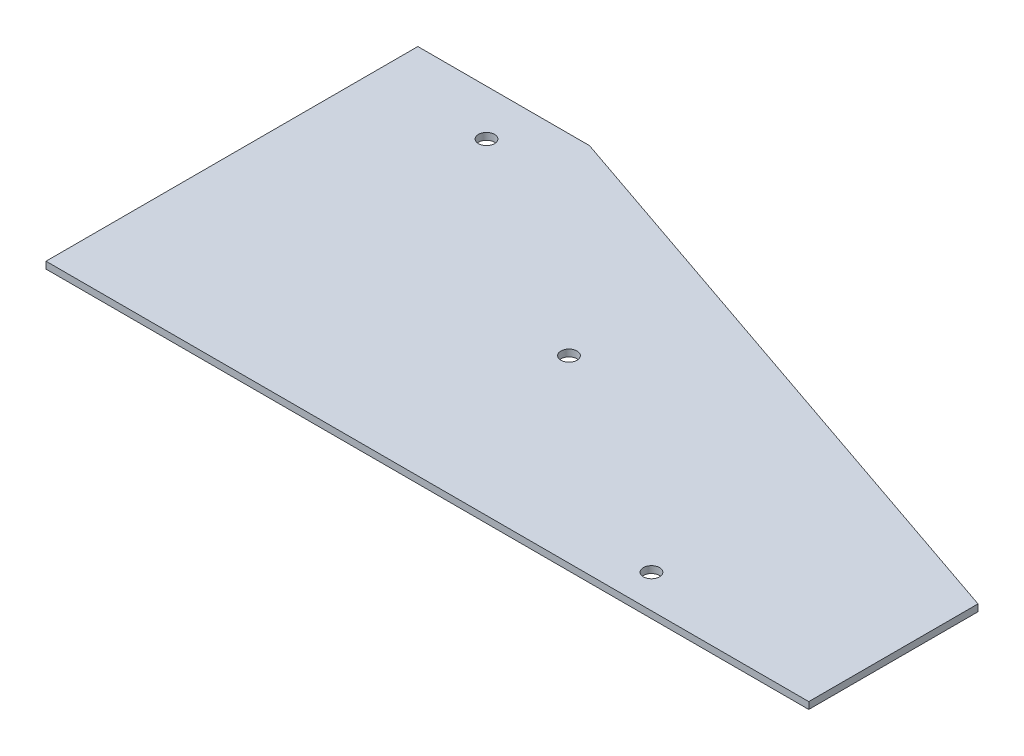
SolidWorks part; units mm, degrees
material "Pine"
ref_plane "Front Plane" through (0, 0, 0) normal (0, 0, 1) x (1, 0, 0)
ref_plane "Top Plane" through (0, 0, 0) normal (0, 1, 0) x (1, 0, 0)
ref_plane "Right Plane" through (0, 0, 0) normal (1, 0, 0) x (0, 0, -1)
sketch "Sketch1" plane through (0, 0, 0) normal (0, 1, 0) x (1, 0, 0)
  line L0 (2032, 450.85) -> (457.2, 990.6)
  line L1 (0, 0) -> (2032, 0)
  line L2 (0, 0) -> (0, 990.6)
  line L3 (0, 990.6) -> (2032, 990.6) construction
  line L4 (2032, 0) -> (2032, 990.6) construction
  line L5 (0, 990.6) -> (457.2, 990.6)
  line L6 (2032, 450.85) -> (2032, 0)
  dimension "D1" = 2032
  dimension "D2" = 990.6
  dimension "D3" = 457.2
  dimension "D4" = 450.85
extrude "Boss-Extrude1" add sketch "Sketch1" along normal blind 18.2562
hole_wizard "1 (1.69) Diameter Hole1" positions "Sketch2" profile "Sketch3" hole size "1" standard "ANSI Inch" end condition through all
sketch "Sketch2" plane through (0, 18.2562, 0) normal (0, 1, 0) x (1, 0, 0)
  line L0 (0, 0) -> (2032, 0) construction
  line L3 (0, 990.6) -> (0, 0) construction
  line L4 (2032, 0) -> (2032, 450.85) construction
  line L5 (457.2, 990.6) -> (0, 990.6) construction
  point P0 (1524, 88.9)
  point P2 (914.4, 478.79)
  point P4 (304.8, 868.68)
  dimension "D1" = 609.6
  dimension "D2" = 609.6
  dimension "D3" = 389.89
  dimension "D4" = 389.89
  dimension "D5" = 88.9
  dimension "D8" = 304.8
  dimension "D7" = 508
  dimension "D6" = 121.92
sketch "Sketch3" plane through (1524, 18.2562, -88.9) normal (1, 0, 0) x (0, 0, 1)
  line L0 (0, 0) -> (0, 18.2562)
  line L1 (0, 18.2562) -> (21.463, 18.2562)
  line L2 (21.463, 18.2562) -> (21.463, 0)
  line L5 (21.463, 0) -> (0, 0)
  line L11 (0, -6.35) -> (0, 107.95) construction
  dimension "Thru Hole Dia." = 42.926
  dimension "Thru Hole Depth" = 18.2562
equation "\"D4@Sketch2\"=\"D3@Sketch2\""
